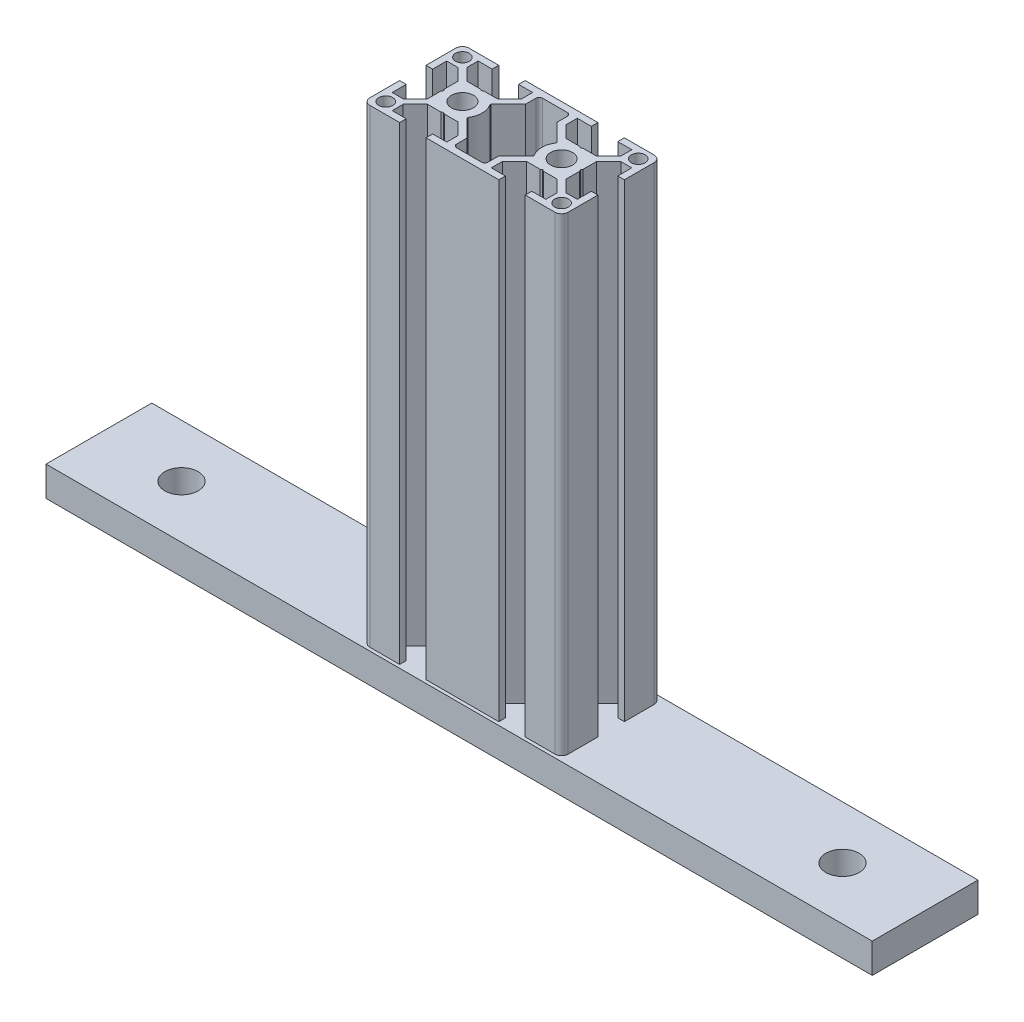
SolidWorks part; units mm, degrees
ref_plane "Front Plane" through (0, 0, 0) normal (0, 0, 1) x (1, 0, 0)
ref_plane "Top Plane" through (0, 0, 0) normal (0, 1, 0) x (1, 0, 0)
ref_plane "Right Plane" through (0, 0, 0) normal (1, 0, 0) x (0, 0, -1)
ref_plane "Plane1" through (0, 70, 0) normal (0, 1, 0) x (1, 0, 0)
sketch "Sketch1" plane through (0, 0, 0) normal (1, 0, 0) x (0, 0, -1)
  line L0 (0, 0) -> (0, 79) construction
  line L1 (17.6, 70) -> (-17.6, 70) construction
  line L2 (-16, 79) -> (16, 79)
  line L3 (-16, 79) -> (-16, 70)
  line L4 (-16, 70) -> (16, 70)
  line L5 (16, 79) -> (16, 70)
  dimension "FIX_2" = 9
  dimension "FIX_3" = 32
extrude "Boss-Extrude1" add sketch "Sketch1" along normal mid plane 250
hole_wizard "Tap1" positions "Sketch3" profile "Sketch2" hole size "M12x1.75" standard "JIS" end condition through all
sketch "Sketch3" plane through (0, 79, 0) normal (0, 1, 0) x (1, 0, 0)
  line L0 (0, 0) -> (0, 16) construction
  line L2 (125, 16) -> (-125, 16) construction
  line L3 (-87.45, 0) -> (87.45, 0) construction
  point P0 (-100, 0)
  point P2 (100, 0)
  dimension "D" = 200
cosmetic thread "Thread1" parameters "HTD"=12
cosmetic thread "Thread2" parameters "HTD"=12
sketch "Sketch2" plane through (-100, 79, 0) normal (1, 0, 0) x (0, 0, 1)
  line L0 (0, 0) -> (0, 9)
  line L1 (0, 9) -> (5.053, 9)
  line L2 (5.053, 9) -> (5.053, 0)
  line L5 (5.053, 0) -> (0, 0)
  line L11 (0, -6.35) -> (0, 107.95) construction
  dimension "Thru Hole Dia." = 10.106
  dimension "Thru Hole Depth" = 9
sketch "Sketch4" plane through (0, 79, 0) normal (0, 1, 0) x (1, 0, 0)
  line L0 (-15, 0) -> (15, 0) construction
  line L1 (0, 16) -> (0, -16) construction
  line L2 (-87.45, 0) -> (87.45, 0) construction
  line L3 (125, 16) -> (-125, 16) construction
  line L4 (125, -16) -> (-125, -16) construction
  circle A0 centre (-15, 0) radius 4.5
  circle A1 centre (15, 0) radius 4.5
  dimension "FIX_5" = 9
  dimension "FIX_4" = 30
extrude "Cut-Extrude1" cut sketch "Sketch4" against normal through all
sketch "Sketch5" plane through (0, 79, 0) normal (0, 1, 0) x (1, 0, 0)
  line L0 (4.75, 8.8358) -> (4.75, 12)
  line L1 (3.75, 13) -> (-3.75, 13)
  line L2 (-4.75, 12) -> (-4.75, 8.8358)
  line L3 (-4.75, 8.8358) -> (-9.934, 3.6518)
  line L4 (-9.934, -3.6518) -> (-4.75, -8.8358)
  line L5 (-4.75, -8.8358) -> (-4.75, -12)
  line L6 (-3.75, -13) -> (3.75, -13)
  line L7 (4.75, -12) -> (4.75, -8.8358)
  line L8 (4.75, -8.8358) -> (9.934, -3.6518)
  line L9 (9.934, 3.6518) -> (4.75, 8.8358)
  line L10 (-11, -15) -> (11, -15)
  line L11 (11, -15) -> (11, -13)
  line L12 (11, -13) -> (6.75, -13)
  line L13 (6.75, -13) -> (6.75, -9.6642)
  line L14 (6.75, -9.6642) -> (10.4142, -6)
  line L15 (10.4142, -6) -> (14.4804, -6)
  line L16 (14.4804, -6) -> (15, -5.7)
  line L17 (15, -5.7) -> (15.5196, -6)
  line L18 (15.5196, -6) -> (19.5858, -6)
  line L19 (19.5858, -6) -> (23.25, -9.6642)
  line L20 (23.25, -9.6642) -> (23.25, -13)
  line L21 (23.25, -13) -> (19, -13)
  line L22 (19, -13) -> (19, -15)
  line L23 (19, -15) -> (28, -15)
  line L24 (30, -13) -> (30, -4)
  line L25 (30, -4) -> (28, -4)
  line L26 (28, -4) -> (28, -8.25)
  line L27 (28, -8.25) -> (24.6642, -8.25)
  line L28 (24.6642, -8.25) -> (21, -4.5858)
  line L29 (21, -4.5858) -> (21, -0.5196)
  line L30 (21, -0.5196) -> (20.7, 0)
  line L31 (20.7, 0) -> (21, 0.5196)
  line L32 (21, 0.5196) -> (21, 4.5858)
  line L33 (21, 4.5858) -> (24.6642, 8.25)
  line L34 (24.6642, 8.25) -> (28, 8.25)
  line L35 (28, 8.25) -> (28, 4)
  line L36 (28, 4) -> (30, 4)
  line L37 (30, 4) -> (30, 13)
  line L38 (28, 15) -> (19, 15)
  line L39 (19, 15) -> (19, 13)
  line L40 (19, 13) -> (23.25, 13)
  line L41 (23.25, 13) -> (23.25, 9.6642)
  line L42 (23.25, 9.6642) -> (19.5858, 6)
  line L43 (19.5858, 6) -> (15.5196, 6)
  line L44 (15.5196, 6) -> (15, 5.7)
  line L45 (15, 5.7) -> (14.4804, 6)
  line L46 (14.4804, 6) -> (10.4142, 6)
  line L47 (10.4142, 6) -> (6.75, 9.6642)
  line L48 (6.75, 9.6642) -> (6.75, 13)
  line L49 (6.75, 13) -> (11, 13)
  line L50 (11, 13) -> (11, 15)
  line L51 (11, 15) -> (-11, 15)
  line L52 (-11, 15) -> (-11, 13)
  line L53 (-11, 13) -> (-6.75, 13)
  line L54 (-6.75, 13) -> (-6.75, 9.6642)
  line L55 (-6.75, 9.6642) -> (-10.4142, 6)
  line L56 (-10.4142, 6) -> (-14.4804, 6)
  line L57 (-14.4804, 6) -> (-15, 5.7)
  line L58 (-15, 5.7) -> (-15.5196, 6)
  line L59 (-15.5196, 6) -> (-19.5858, 6)
  line L60 (-19.5858, 6) -> (-23.25, 9.6642)
  line L61 (-23.25, 9.6642) -> (-23.25, 13)
  line L62 (-23.25, 13) -> (-19, 13)
  line L63 (-19, 13) -> (-19, 15)
  line L64 (-19, 15) -> (-28, 15)
  line L65 (-30, 13) -> (-30, 4)
  line L66 (-30, 4) -> (-28, 4)
  line L67 (-28, 4) -> (-28, 8.25)
  line L68 (-28, 8.25) -> (-24.6642, 8.25)
  line L69 (-24.6642, 8.25) -> (-21, 4.5858)
  line L70 (-21, 4.5858) -> (-21, 0.5196)
  line L71 (-21, 0.5196) -> (-20.7, 0)
  line L72 (-20.7, 0) -> (-21, -0.5196)
  line L73 (-21, -0.5196) -> (-21, -4.5858)
  line L74 (-21, -4.5858) -> (-24.6642, -8.25)
  line L75 (-24.6642, -8.25) -> (-28, -8.25)
  line L76 (-28, -8.25) -> (-28, -4)
  line L77 (-28, -4) -> (-30, -4)
  line L78 (-30, -4) -> (-30, -13)
  line L79 (-28, -15) -> (-19, -15)
  line L80 (-19, -15) -> (-19, -13)
  line L81 (-19, -13) -> (-23.25, -13)
  line L82 (-23.25, -13) -> (-23.25, -9.6642)
  line L83 (-23.25, -9.6642) -> (-19.5858, -6)
  line L84 (-19.5858, -6) -> (-15.5196, -6)
  line L85 (-15.5196, -6) -> (-15, -5.7)
  line L86 (-15, -5.7) -> (-14.4804, -6)
  line L87 (-14.4804, -6) -> (-10.4142, -6)
  line L88 (-10.4142, -6) -> (-6.75, -9.6642)
  line L89 (-6.75, -9.6642) -> (-6.75, -13)
  line L90 (-6.75, -13) -> (-11, -13)
  line L91 (-11, -13) -> (-11, -15)
  arc A0 (28, -15) -> (30, -13) centre (28, -13) ccw
  arc A1 (30, 13) -> (28, 15) centre (28, 13) ccw
  arc A2 (-28, 15) -> (-30, 13) centre (-28, 13) ccw
  arc A3 (-30, -13) -> (-28, -15) centre (-28, -13) ccw
  circle A4 centre (-26.6, -11.6) radius 2.1
  circle A5 centre (-26.6, 11.6) radius 2.1
  circle A6 centre (-15, 0) radius 3.3235
  circle A7 centre (26.6, -11.6) radius 2.1
  circle A8 centre (15, 0) radius 3.3235
  circle A9 centre (26.6, 11.6) radius 2.1
  arc A10 (4.75, 12) -> (3.75, 13) centre (3.75, 12) ccw
  arc A11 (-3.75, 13) -> (-4.75, 12) centre (-3.75, 12) ccw
  arc A12 (-9.934, 3.6518) -> (-9.9732, 3.2759) centre (-9.7219, 3.4397) ccw
  arc A13 (-9.9732, -3.2759) -> (-9.9732, 3.2759) centre (-15, 0) ccw
  arc A14 (-9.9732, -3.2759) -> (-9.934, -3.6518) centre (-9.7219, -3.4397) ccw
  arc A15 (-4.75, -12) -> (-3.75, -13) centre (-3.75, -12) ccw
  arc A16 (3.75, -13) -> (4.75, -12) centre (3.75, -12) ccw
  arc A17 (9.934, -3.6518) -> (9.9732, -3.2759) centre (9.7219, -3.4397) ccw
  arc A18 (9.9732, 3.2759) -> (9.9732, -3.2759) centre (15, 0) ccw
  arc A19 (9.9732, 3.2759) -> (9.934, 3.6518) centre (9.7219, 3.4397) ccw
extrude "Boss-Extrude2" add sketch "Sketch5" along normal blind 142
sketch "Sketch6" plane through (0, 0, 0) normal (0, 0, 1) x (1, 0, 0)
  line L0 (15, 62) -> (15, 95) construction
  line L1 (18, 62) -> (21.5, 62)
  line L2 (21.5, 62) -> (21.5, 70)
  line L3 (21.5, 70) -> (19, 70)
  line L4 (19, 70) -> (19, 95)
  line L5 (19, 95) -> (15, 95)
  line L6 (15, 95) -> (15, 67.7321)
  line L8 (18, 62) -> (18, 66)
  line L9 (18, 66) -> (15, 67.7321)
  line L10 (15, 67.7321) -> (12, 66) construction
  line L11 (12, 66) -> (18, 66) construction
  dimension "FIX_6" = 25
  dimension "FIX_7" = 8
  dimension "FIX_8" = 13
  dimension "FIX_9" = 8
  dimension "FIX_10" = 6
  dimension "FIX_11" = 120
  dimension "FIX_12" = 4
revolve "Revolve1" add sketch "Sketch6" angle 360 about L6
sketch "Sketch7" plane through (0, 62, 0) normal (0, -1, 0) x (1, 0, 0)
  line L0 (4.95, 0) -> (-4.95, 0) construction
  line L1 (18.4641, 0) -> (16.7321, 3)
  line L2 (16.7321, 3) -> (13.2679, 3)
  line L3 (13.2679, 3) -> (11.5359, 0)
  line L4 (11.5359, 0) -> (13.2679, -3)
  line L5 (13.2679, -3) -> (16.7321, -3)
  line L6 (16.7321, -3) -> (18.4641, 0)
  circle A0 centre (15, 0) radius 3 construction
  dimension "FIX_14" = 6
extrude "Cut-Extrude2" cut sketch "Sketch7" against normal blind 4
chamfer "Chamfer1" distance 0.3 1 edges at (8.5, 62, 0)
mirror "Mirror1" about plane through (0, 0, 0) normal (1, 0, 0) of "Chamfer1", "Cut-Extrude2", "Revolve1"
ref_plane "Plane2" through (0, 124, 0) normal (0, 1, 0) x (1, 0, 0)
equation "\"H\"= 300"
equation "\"C\"= 21"
equation "\"KSS_2@Boss-Extrude2\"= \"H\" - \"C\" - 58 - 9 - 70"
equation "\"KSS_1@Boss-Extrude1\" = \"D@Sketch3\" + 50"
equation "\"B\"= 30"
equation "\"D@Sketch3\"= if ( \"B\" < = 80 , 200 , 280 )"
